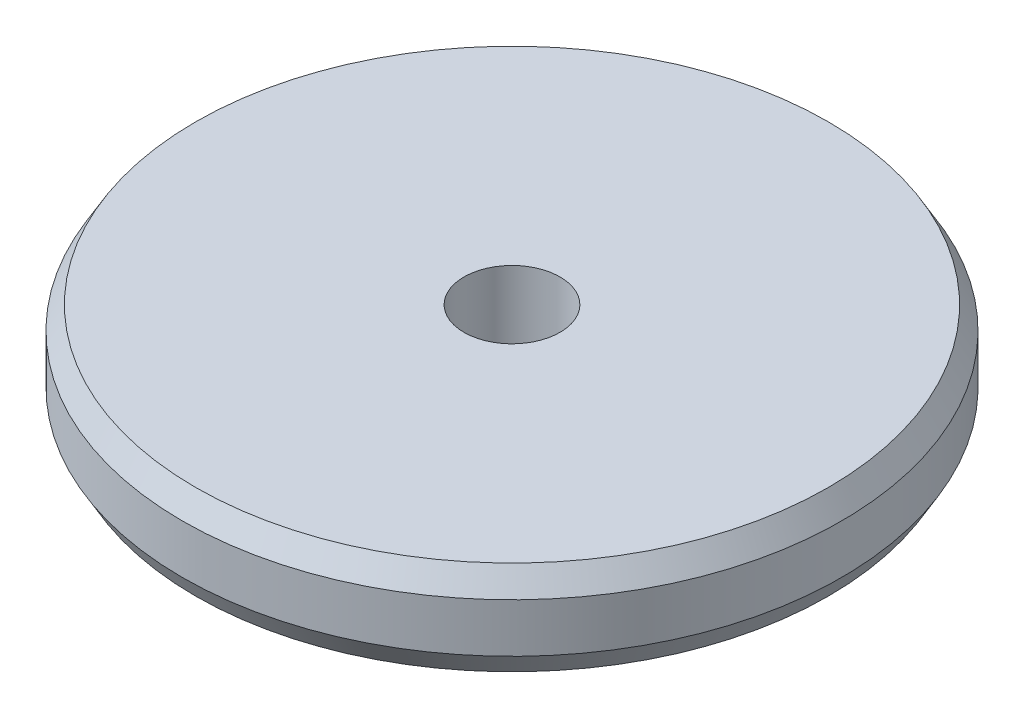
SolidWorks part; units mm, degrees
ref_plane "정면" through (0, 0, 0) normal (0, 0, 1) x (1, 0, 0)
ref_plane "윗면" through (0, 0, 0) normal (0, 1, 0) x (1, 0, 0)
ref_plane "우측면" through (0, 0, 0) normal (1, 0, 0) x (0, 0, -1)
sketch "스케치1" plane through (0, 0, 0) normal (0, 1, 0) x (1, 0, 0)
  circle A0 centre (0, 0) radius 17.5
  dimension "D1" = 35
extrude "보스-돌출1" add sketch "스케치1" along normal blind 5
sketch "스케치2" plane through (0, 5, 0) normal (0, 1, 0) x (1, 0, 0)
  circle A0 centre (0, 0) radius 2.55
  dimension "D1" = 5.1
extrude "컷-돌출1" cut sketch "스케치2" against normal through all both and the other way through all
chamfer "모따기1" distance 1.2 angle 30 2 edges at (0, 0, 17.5) (0, 5, 17.5)
